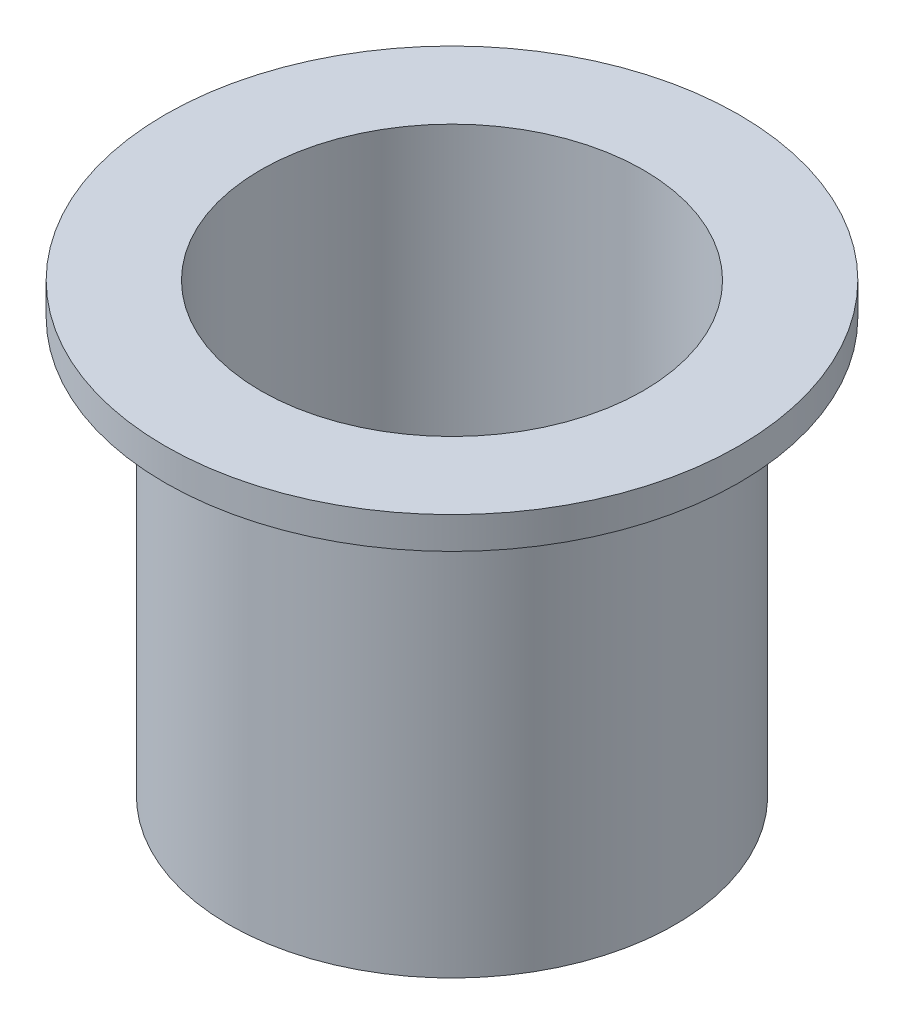
SolidWorks part; units mm, degrees
ref_plane "Front Plane" through (0, 0, 0) normal (0, 0, 1) x (1, 0, 0)
ref_plane "Top Plane" through (0, 0, 0) normal (0, 1, 0) x (1, 0, 0)
ref_plane "Right Plane" through (0, 0, 0) normal (1, 0, 0) x (0, 0, -1)
sketch "Sketch1" plane through (0, 0, 0) normal (0, 1, 0) x (1, 0, 0)
  circle A0 centre (0, 0) radius 7
  dimension "D1" = 14
extrude "Boss-Extrude1" add sketch "Sketch1" along normal blind 13
shell "Shell2" thickness 1
sketch "Sketch2" plane through (0, 0, 0) normal (0, -1, 0) x (1, 0, 0)
  circle A0 centre (0, 0) radius 2.5
  dimension "D1" = 5
extrude "Cut-Extrude1" cut sketch "Sketch2" against normal blind 10 contours A0
sketch "Sketch3" plane through (0, 13, 0) normal (0, 1, 0) x (1, 0, 0)
  circle A0 centre (0, 0) radius 9
  dimension "D1" = 18
extrude "Boss-Extrude2" add sketch "Sketch3" along normal blind 1
sketch "Sketch4" plane through (0, 14, 0) normal (0, 1, 0) x (1, 0, 0)
  circle A0 centre (0, 0) radius 6
  dimension "D1" = 12
extrude "Cut-Extrude2" cut sketch "Sketch4" against normal blind 2
